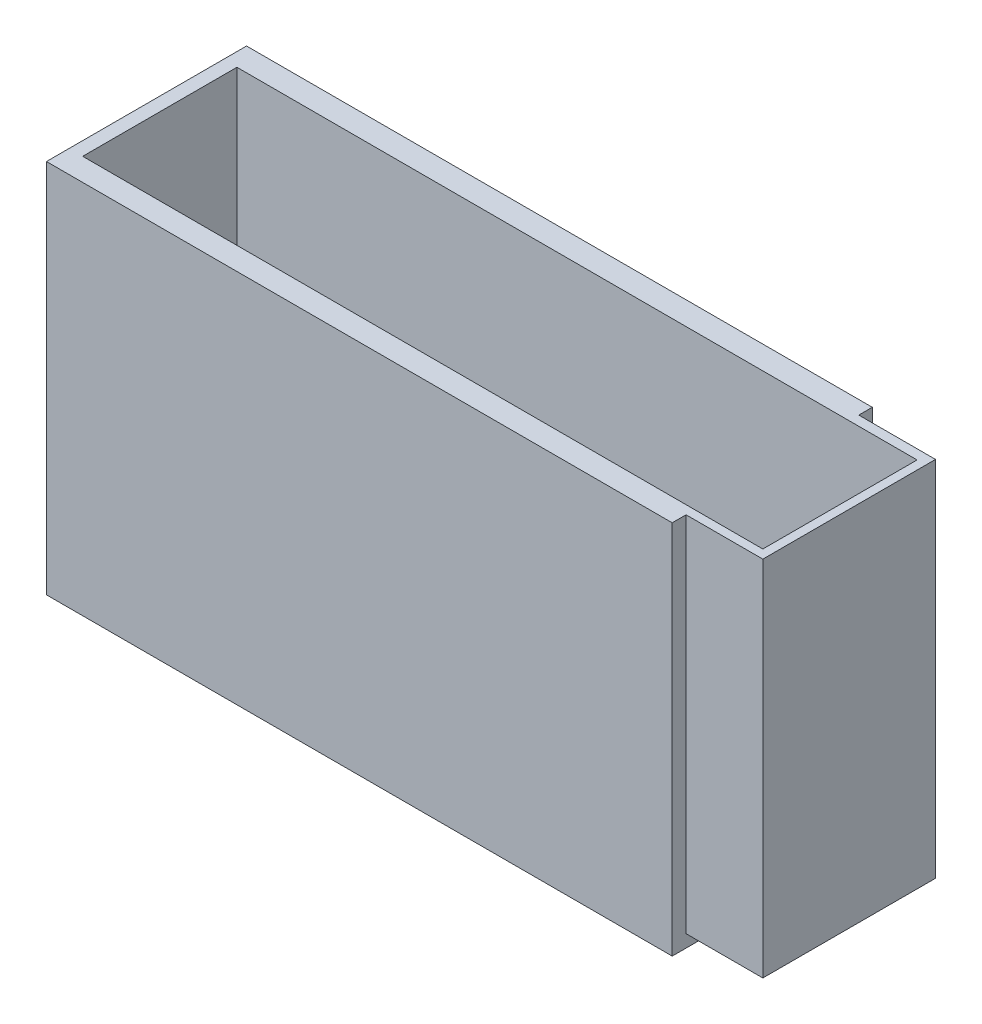
SolidWorks part; units mm, degrees
ref_plane "Front Plane" through (0, 0, 0) normal (0, 0, 1) x (1, 0, 0)
ref_plane "Top Plane" through (0, 0, 0) normal (0, 1, 0) x (1, 0, 0)
ref_plane "Right Plane" through (0, 0, 0) normal (1, 0, 0) x (0, 0, -1)
sketch "Sketch5" plane through (0, 0, 0) normal (0, 1, 0) x (1, 0, 0)
  line L1 (-190.6691, 115.4866) -> (126.9739, 115.4866)
  line L2 (-190.6691, 115.4866) -> (-190.6691, 13.9207)
  line L3 (-190.6691, 13.9207) -> (126.9739, 13.9207)
  line L4 (126.9739, 115.4866) -> (126.9739, 13.9207)
  line L5 (-190.6691, 115.4866) -> (126.9739, 13.9207) construction
  line L6 (-190.6691, 13.9207) -> (126.9739, 115.4866) construction
  point P0 (-31.8476, 64.7037)
extrude "Boss-Extrude3" add sketch "Sketch5" along normal blind 190.5
sketch "Sketch11" plane through (0, 190.5, 0) normal (0, 1, 0) x (1, 0, 0)
  line L0 (126.9739, 13.9207) -> (126.9739, 115.4866) construction
  line L1 (-183.3078, 108.6212) -> (126.9739, 108.6212)
  line L2 (-183.3078, 108.6212) -> (-183.3078, 20.9568)
  line L3 (-183.3078, 20.9568) -> (126.9739, 20.9568)
  line L4 (126.9739, 108.6212) -> (126.9739, 20.9568)
  line L5 (-183.3078, 108.6212) -> (126.9739, 20.9568) construction
  line L6 (-183.3078, 20.9568) -> (126.9739, 108.6212) construction
  line L7 (126.9739, 13.9207) -> (126.9739, 115.4866) construction
  point P0 (-28.1669, 64.789)
  point P5 (126.9739, 17.6409)
  point P8 (-183.9295, 17.8482)
  point P9 (-179.3702, 102.8184)
  point P10 (-183.3078, 108.6212)
  point P11 (126.9739, 20.9568)
  point P12 (0, 0)
  dimension "D1" = 87.6644
  dimension "D2" = 310.2817
extrude "Cut-Extrude2" cut sketch "Sketch11" against normal blind 184.15
sketch "Sketch14" plane through (-183.3078, 0, 0) normal (1, 0, 0) x (0, 0, -1)
  line L1 (20.9568, 190.5) -> (108.6212, 190.5)
  line L2 (20.9568, 190.5) -> (20.9568, 6.35)
  line L3 (20.9568, 6.35) -> (108.6212, 6.35)
  line L4 (108.6212, 190.5) -> (108.6212, 6.35)
  point P6 (20.9568, 190.5)
extrude "Boss-Extrude5" add sketch "Sketch14" along normal blind 349.25
sketch "Sketch18" plane through (0, 190.5, 0) normal (0, 1, 0) x (1, 0, 0)
  line L1 (161.5005, 103.6997) -> (-183.7612, 103.6997)
  line L2 (161.5005, 103.6997) -> (161.5005, 25.3993)
  line L3 (161.5005, 25.3993) -> (-183.7612, 25.3993)
  line L4 (-183.7612, 103.6997) -> (-183.7612, 25.3993)
extrude "Cut-Extrude3" cut sketch "Sketch18" against normal blind 181.61
